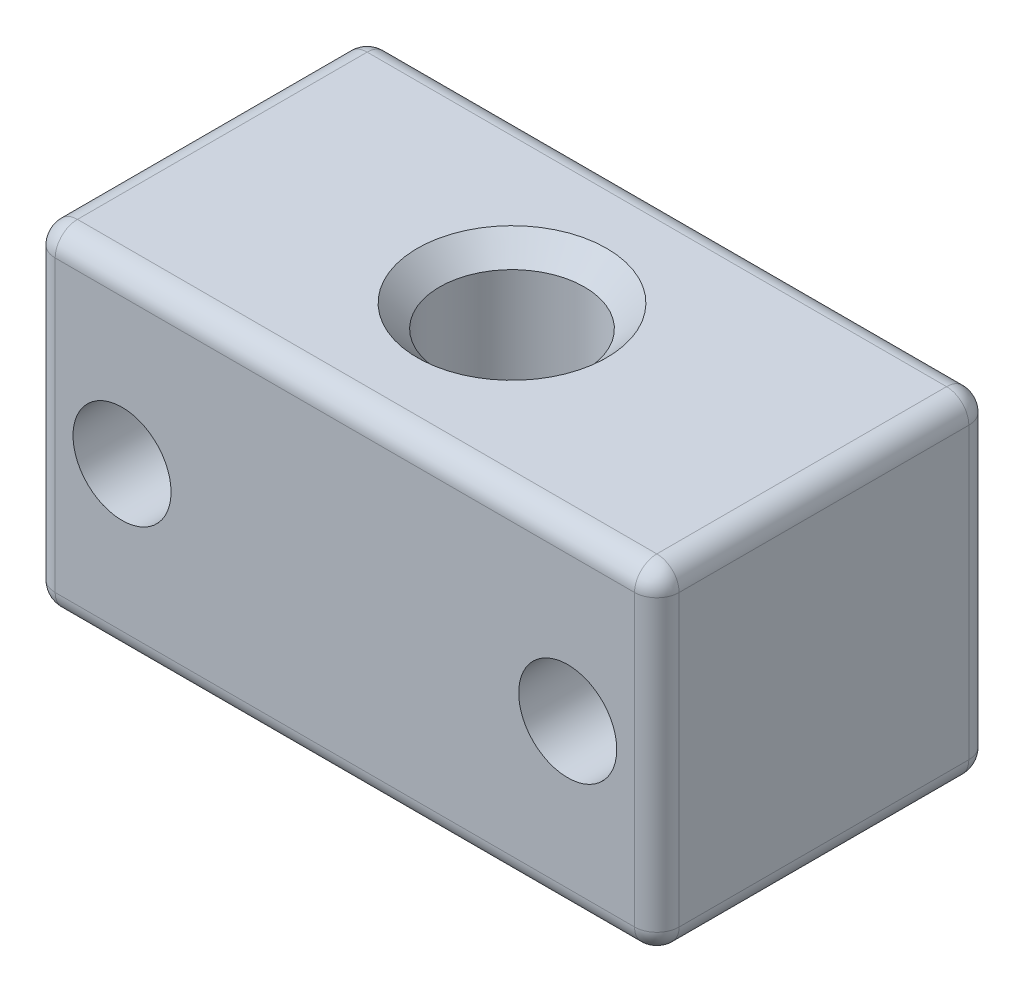
SolidWorks part; units mm, degrees
ref_plane "前视基准面" through (0, 0, 0) normal (0, 0, 1) x (1, 0, 0)
ref_plane "上视基准面" through (0, 0, 0) normal (0, 1, 0) x (1, 0, 0)
ref_plane "右视基准面" through (0, 0, 0) normal (1, 0, 0) x (0, 0, -1)
other "Configuration Table"
sketch "草图1" plane through (0, 0, 0) normal (0, 1, 0) x (1, 0, 0)
  line L1 (-14, -7.5) -> (14, -7.5)
  line L2 (-14, -7.5) -> (-14, 7.5)
  line L3 (-14, 7.5) -> (14, 7.5)
  line L4 (14, -7.5) -> (14, 7.5)
  line L5 (-14, -7.5) -> (14, 7.5) construction
  line L6 (-14, 7.5) -> (14, -7.5) construction
  circle A0 centre (0, 0) radius 3.25
  point P0 (0, 0)
  dimension "D3" = 6.5
  dimension "D1" = 28
  dimension "D2" = 15
extrude "凸台-拉伸1" add sketch "草图1" along normal mid plane 15
sketch "草图2" plane through (0, 0, 7.5) normal (0, 0, 1) x (1, 0, 0)
  circle A0 centre (-10, 0) radius 2.2
  circle A1 centre (10, 0) radius 2.2
  dimension "D1" = 4.4
  dimension "D2" = 20
  dimension "D3" = 10
extrude "切除-拉伸1" cut sketch "草图2" against normal blind 15
fillet "圆角1" radius 1 12 edges at (14, 0, 7.5) (14, 7.5, 0) (14, 0, -7.5) (14, -7.5, 0) (-14, 0, -7.5) (-14, 7.5, 0) (-14, 0, 7.5) (-14, -7.5, 0) (0, -7.5, -7.5) (0, -7.5, 7.5) (0, 7.5, -7.5) (0, 7.5, 7.5)
chamfer "倒角1" distance 1 angle 45 2 edges at (0, -7.5, 3.25) (0, 7.5, 3.25)
